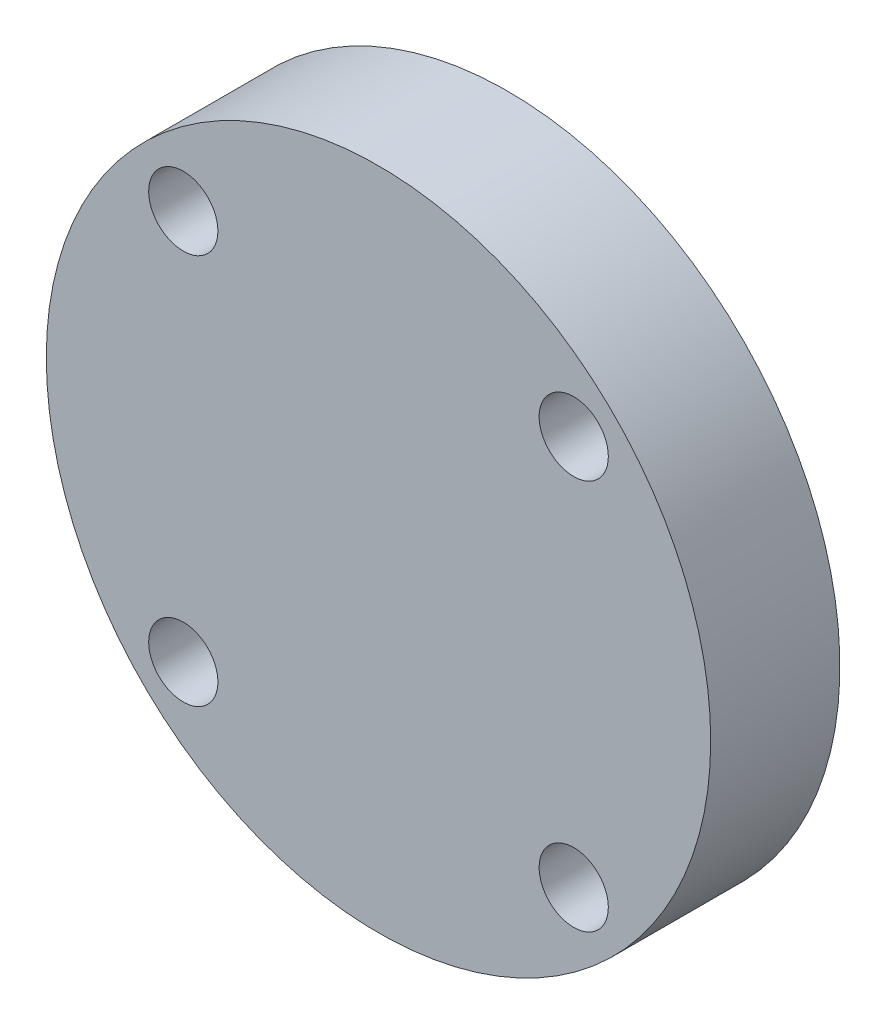
SolidWorks part; units mm, degrees
ref_plane "Front Plane" through (0, 0, 0) normal (0, 0, 1) x (1, 0, 0)
ref_plane "Top Plane" through (0, 0, 0) normal (0, 1, 0) x (1, 0, 0)
ref_plane "Right Plane" through (0, 0, 0) normal (1, 0, 0) x (0, 0, -1)
sketch "Sketch1" plane through (0, 0, 0) normal (0, 0, 1) x (1, 0, 0)
  circle A0 centre (0, 0) radius 114.3
  dimension "D1" = 228.6
extrude "Boss-Extrude1" add sketch "Sketch1" along normal mid plane 50.8
sketch "Sketch2" plane through (0, 0, -25.4) normal (0, 0, -1) x (-1, 0, 0)
  circle A0 centre (0, 0) radius 68.2498
  circle A1 centre (0, 0) radius 114.3 construction
  circle A2 centre (0, 0) radius 114.3
  dimension "D1" = 136.4996
extrude "Cut-Extrude1" cut sketch "Sketch2" against normal blind 6.35
sketch "Sketch3" plane through (0, 0, -19.05) normal (0, 0, -1) x (-1, 0, 0)
  circle A0 centre (0, 0) radius 77.9399
  circle A1 centre (0, 0) radius 73.3679
  dimension "D2" = 155.8798
  dimension "D1" = 4.572
extrude "Cut-Extrude2" cut sketch "Sketch3" against normal blind 2.5654
sketch "Sketch4" plane through (0, 0, 25.4) normal (0, 0, 1) x (1, 0, 0)
  line L0 (0, 0) -> (0, 94.996) construction
  line L1 (0, 0) -> (67.1723, 67.1723) construction
  circle A0 centre (0, 0) radius 94.996 construction
  dimension "D1" = 189.992
  dimension "D2" = 45
sketch "Sketch5" plane through (0, 0, 25.4) normal (0, 0, 1) x (1, 0, 0)
  circle A0 centre (67.1723, 67.1723) radius 11.9063
  dimension "D1" = 23.8125
extrude "Cut-Extrude3" cut sketch "Sketch5" against normal up to next
pattern_circular "CirPattern1" count 4 over 360 about axis through (0, 0, 0) along (0, 0, 1) of "Cut-Extrude3"
